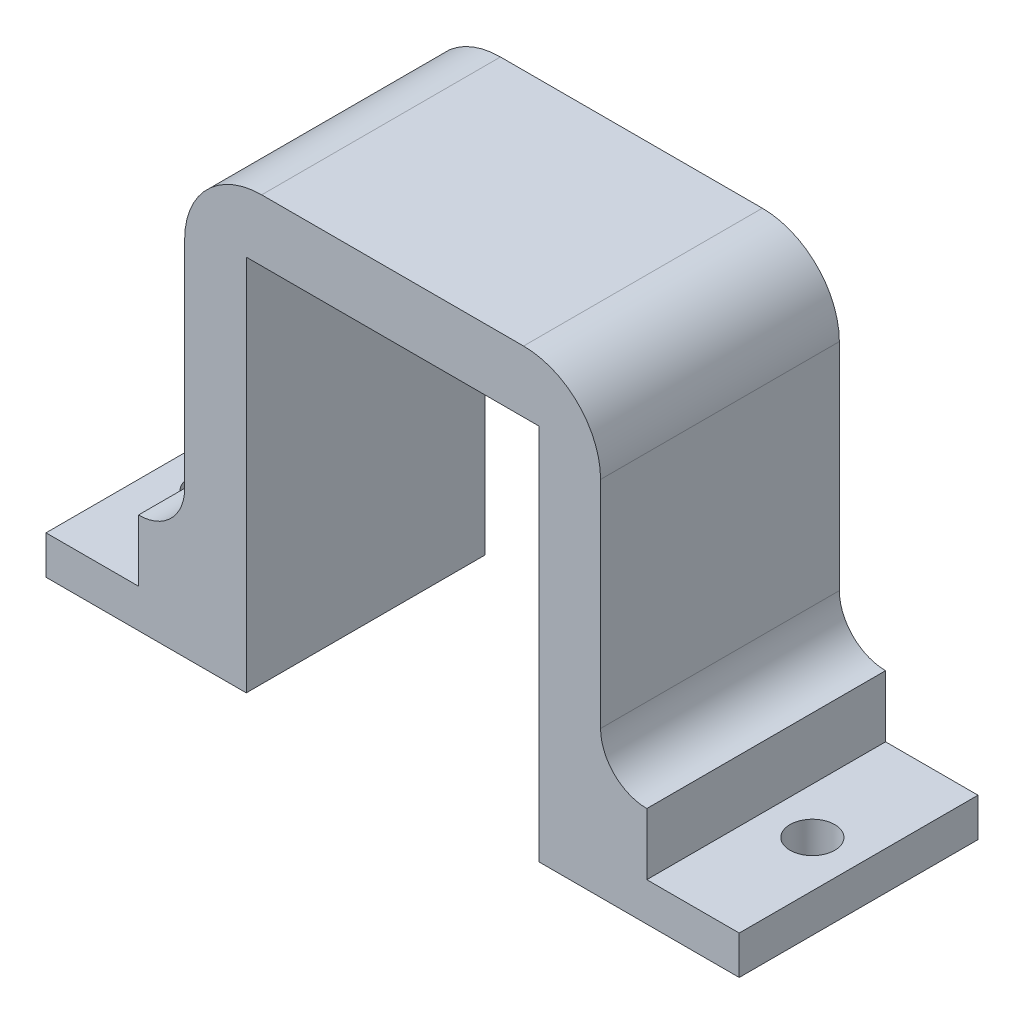
SolidWorks part; units mm, degrees
ref_plane "Front Plane" through (0, 0, 0) normal (0, 0, 1) x (1, 0, 0)
ref_plane "Top Plane" through (0, 0, 0) normal (0, 1, 0) x (1, 0, 0)
ref_plane "Right Plane" through (0, 0, 0) normal (1, 0, 0) x (0, 0, -1)
sketch "Sketch1" plane through (0, 0, 0) normal (0, 0, 1) x (1, 0, 0)
  line L0 (0, 3) -> (0, 17)
  line L1 (5, 22) -> (22, 22)
  line L2 (27, 17) -> (27, 3)
  line L3 (30, 0) -> (36, 0)
  line L4 (36, 0) -> (36, -4)
  line L5 (36, -4) -> (23, -4)
  line L6 (23, -4) -> (23, 18)
  line L7 (23, 18) -> (4, 18)
  line L8 (4, 18) -> (4, -4)
  line L9 (4, -4) -> (-9, -4)
  line L10 (-9, -4) -> (-9, 0)
  line L11 (-9, 0) -> (-3, 0)
  arc A0 (5, 22) -> (0, 17) centre (5, 17) ccw
  arc A1 (22, 22) -> (27, 17) centre (22, 17) cw
  arc A2 (0, 3) -> (-3, 0) centre (-3, 3) cw
  arc A3 (30, 0) -> (27, 3) centre (30, 3) cw
  point P18 (27, 22)
  point P21 (0, 0)
  dimension "D10" = 5
  dimension "D11" = 3
  dimension "D1" = 19
  dimension "D2" = 4
  dimension "D3" = 4
  dimension "D4" = 4
  dimension "D5" = 4
  dimension "D6" = 4
  dimension "D7" = 22
  dimension "D8" = 13
  dimension "D9" = 13
extrude "Boss-Extrude1" add sketch "Sketch1" along normal blind 23
ref_plane "Plane1" through (13.5, 0, 0) normal (1, 0, 0) x (0, 0, -1)
sketch "Sketch3" plane through (0, 0, 0) normal (0, 1, 0) x (1, 0, 0)
  line L0 (-9, -11.5) -> (36, -11.5) construction
  line L1 (-9, -23) -> (-9, 0) construction
  line L2 (36, -23) -> (36, 0) construction
  line L3 (13.5, -12.1) -> (13.5, 12.1) construction
  line L4 (36, 0) -> (30, 0) construction
  line L6 (36, -23) -> (30, -23) construction
  circle A0 centre (-6, -2.25) radius 1.45
  circle A1 centre (-6, -20.75) radius 1.45
  circle A2 centre (33, -20.75) radius 1.45
  circle A3 centre (33, -2.25) radius 1.45
  point P23 (33, -23)
  dimension "D1" = 2.9
  dimension "D2" = 2.25
  dimension "D3" = 2.25
sketch "Sketch4" plane through (0, 0, 0) normal (-1, 0, 0) x (0, 0, 1)
  line L0 (23, 17) -> (0, 17) construction
  line L1 (4, 17) -> (7.5, 17)
  line L2 (4, 17) -> (4, -4)
  line L3 (4, -4) -> (7.5, -4)
  line L4 (7.5, 17) -> (7.5, -4)
  line L5 (23, -4) -> (0, -4) construction
  line L7 (0, 0) -> (0, -4) construction
  dimension "D1" = 4
  dimension "D2" = 3.5
extrude "Cut-Extrude2" cut sketch "Sketch4" against normal blind 10 and the other way blind 23
sketch "Sketch5" plane through (0, 22, 0) normal (0, 1, 0) x (1, 0, 0)
  line L0 (-9, -7.5) -> (36, -7.5) construction
  line L1 (36, -23) -> (36, 0) construction
  line L3 (-9, 0) -> (36, 0)
  line L4 (-9, 0) -> (-9, -7.5)
  line L5 (-9, -7.5) -> (36, -7.5)
  line L6 (36, 0) -> (36, -7.5)
extrude "Cut-Extrude3" cut sketch "Sketch5" against normal blind 26
sketch "Sketch7" plane through (0, 0, 0) normal (0, 1, 0) x (1, 0, 0)
  line L0 (13.5, -8.525) -> (13.5, 8.525) construction
  line L3 (-3, -23) -> (-9, -23) construction
  line L5 (36, -7.5) -> (30, -7.5) construction
  circle A0 centre (-6, -15.25) radius 1.45
  circle A1 centre (33, -15.25) radius 1.45
  point P14 (-6, -23)
  dimension "D1" = 2.9
  dimension "D2" = 7.75
extrude "Cut-Extrude4" cut sketch "Sketch7" against normal blind 50
sketch "Sketch8" plane through (0, -4, 0) normal (0, -1, 0) x (1, 0, 0)
  line L0 (13.5, -8.525) -> (13.5, 8.525) construction
  line L1 (23, 23) -> (36, 23)
  line L2 (23, 23) -> (23, 7.5)
  line L3 (23, 7.5) -> (36, 7.5)
  line L4 (36, 23) -> (36, 7.5)
  line L5 (4, 7.5) -> (-9, 7.5)
  line L6 (-9, 23) -> (-9, 7.5)
  line L7 (4, 23) -> (-9, 23)
  line L8 (4, 23) -> (4, 7.5)
extrude "Boss-Extrude2" add sketch "Sketch8" along normal blind 2.5
sketch "Sketch9" plane through (0, -4, 0) normal (0, 1, 0) x (1, 0, 0)
  line L0 (13.5, -8.525) -> (13.5, 8.525) construction
  circle A0 centre (33, -15.25) radius 1.45
  circle A1 centre (-6, -15.25) radius 1.45
extrude "Cut-Extrude5" cut sketch "Sketch9" against normal blind 10
sketch "Sketch10" plane through (-9, 0, 0) normal (-1, 0, 0) x (0, 0, 1)
  line L0 (23, 0) -> (23, -6.5) construction
  line L1 (7.5, 0) -> (23, 0)
  line L2 (7.5, 0) -> (7.5, -4)
  line L3 (7.5, -4) -> (23, -4)
  line L4 (23, 0) -> (23, -4)
  dimension "D1" = 4
extrude "Cut-Extrude7" cut sketch "Sketch10" against normal blind 6
sketch "Sketch11" plane through (36, 0, 0) normal (1, 0, 0) x (0, 0, -1)
  line L1 (-23, 0) -> (-7.5, 0)
  line L2 (-23, 0) -> (-23, -4)
  line L3 (-23, -4) -> (-7.5, -4)
  line L4 (-7.5, 0) -> (-7.5, -4)
extrude "Cut-Extrude8" cut sketch "Sketch11" against normal blind 6
